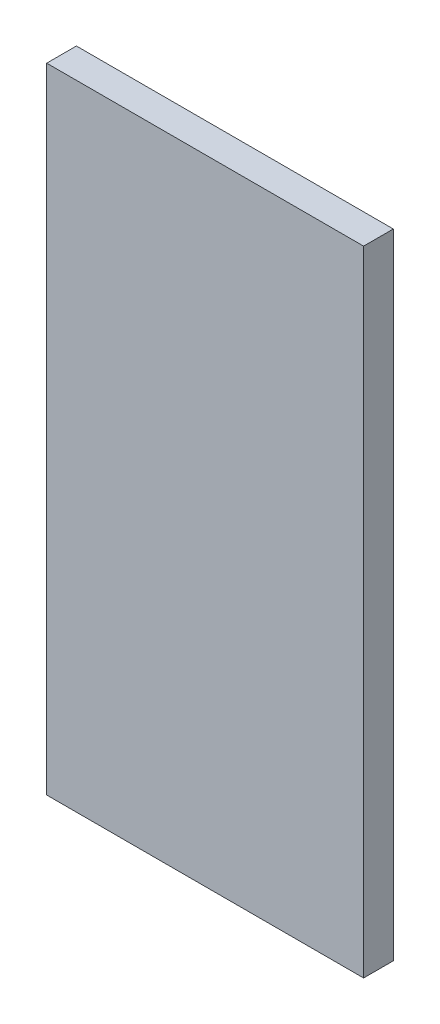
SolidWorks part; units mm, degrees
ref_plane "Front Plane" through (0, 0, 0) normal (0, 0, 1) x (1, 0, 0)
ref_plane "Top Plane" through (0, 0, 0) normal (0, 1, 0) x (1, 0, 0)
ref_plane "Right Plane" through (0, 0, 0) normal (1, 0, 0) x (0, 0, -1)
sketch "Sketch1" plane through (0, 0, 0) normal (0, 0, 1) x (1, 0, 0)
  line L1 (0, 0) -> (203.2, 0)
  line L2 (0, 0) -> (0, 406.4)
  line L3 (0, 406.4) -> (203.2, 406.4)
  line L4 (203.2, 0) -> (203.2, 406.4)
  dimension "D1" = 203.2
  dimension "D2" = 406.4
extrude "Boss-Extrude1" add sketch "Sketch1" along normal blind 19.05
